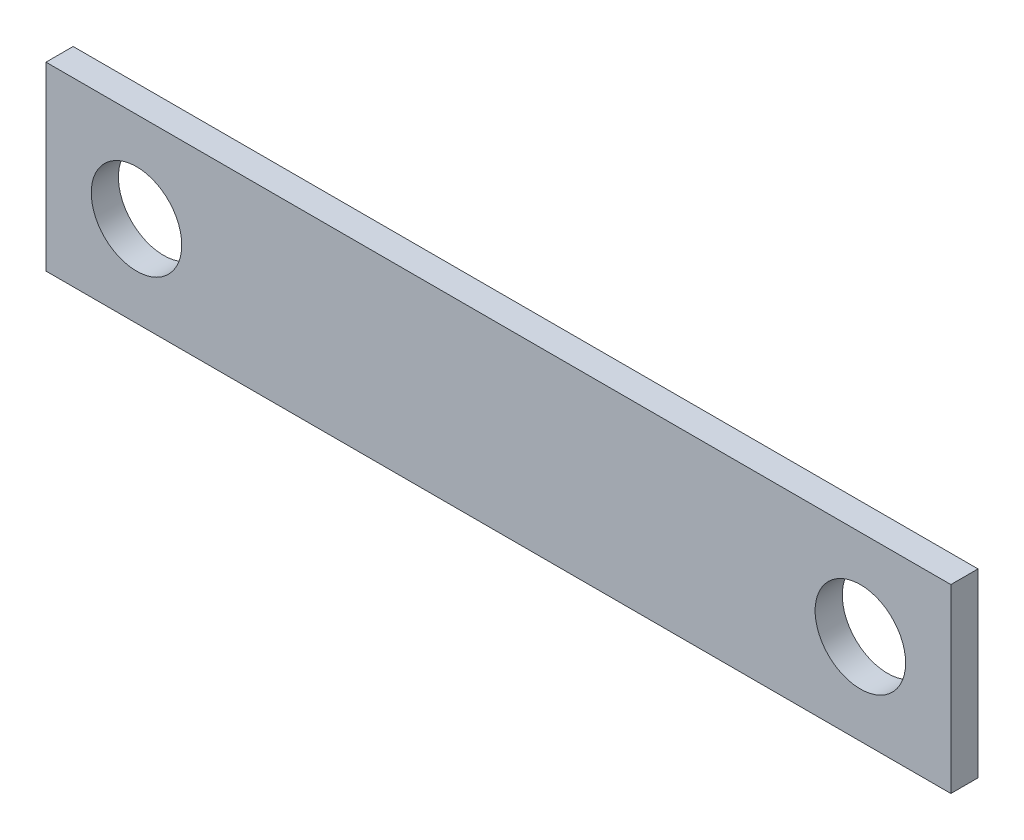
SolidWorks part; units mm, degrees
ref_plane "正面" through (0, 0, 0) normal (0, 0, 1) x (1, 0, 0)
ref_plane "平面" through (0, 0, 0) normal (0, 1, 0) x (1, 0, 0)
ref_plane "右側面" through (0, 0, 0) normal (1, 0, 0) x (0, 0, -1)
sketch "ｽｹｯﾁ1" plane through (0, 0, 0) normal (0, 0, 1) x (1, 0, 0)
  line L1 (0, 0) -> (100, 0)
  line L2 (0, 0) -> (0, 20)
  line L3 (0, 20) -> (100, 20)
  line L4 (100, 0) -> (100, 20)
  dimension "D1" = 100
  dimension "D2" = 20
extrude "ﾎﾞｽ - 押し出し1" add sketch "ｽｹｯﾁ1" along normal blind 3
sketch "ｽｹｯﾁ2" plane through (0, 0, 3) normal (0, 0, 1) x (1, 0, 0)
  line L0 (100, 20) -> (0, 20) construction
  line L1 (0, 20) -> (0, 0) construction
  line L2 (100, 0) -> (100, 20) construction
  line L3 (100, 20) -> (0, 20) construction
  circle A0 centre (10, 10) radius 5
  circle A1 centre (90, 10) radius 5
  dimension "D1" = 10
  dimension "D5" = 10
  dimension "D2" = 10
  dimension "D3" = 10
  dimension "D4" = 10
extrude "ｶｯﾄ - 押し出し1" cut sketch "ｽｹｯﾁ2" against normal blind 3
